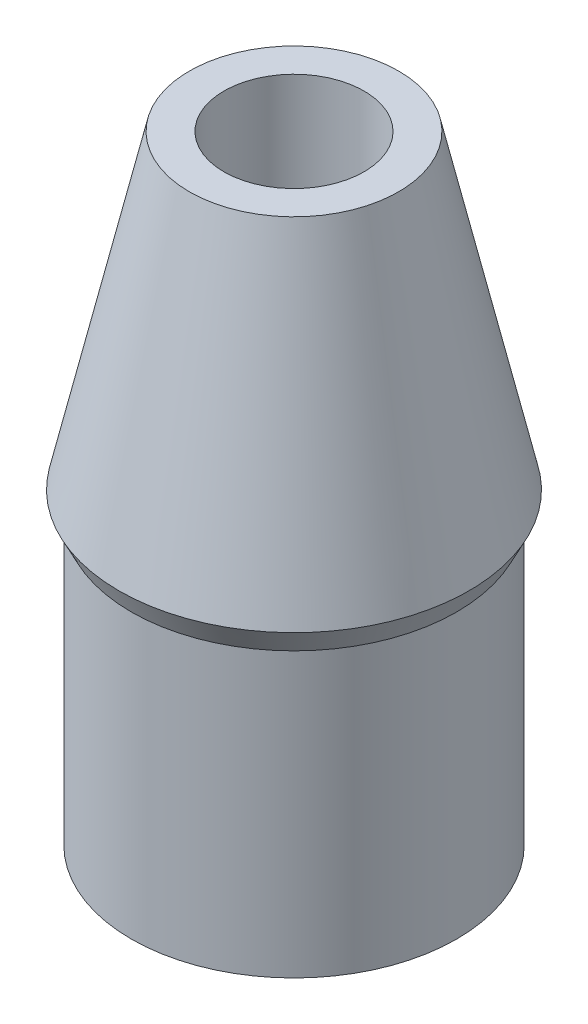
SolidWorks part; units mm, degrees
ref_plane "Front Plane" through (0, 0, 0) normal (0, 0, 1) x (1, 0, 0)
ref_plane "Top Plane" through (0, 0, 0) normal (0, 1, 0) x (1, 0, 0)
ref_plane "Right Plane" through (0, 0, 0) normal (1, 0, 0) x (0, 0, -1)
sketch "Sketch3" plane through (0, 0, 0) normal (0, 0, 1) x (1, 0, 0)
  line L0 (0, 16.51) -> (0, -13.97) construction
  line L1 (8.0264, -13.97) -> (0, -13.97)
  line L2 (5.1599, 16.51) -> (0, 16.51)
  line L3 (0, 16.51) -> (0, -13.97)
  line L7 (8.0264, 0) -> (8.0264, -13.97)
  line L10 (8.0264, 0) -> (8.6308, 1.204)
  line L11 (8.6308, 1.204) -> (5.1599, 16.51)
  dimension "D1" = 16.51
  dimension "D2" = 13.97
  dimension "D3" = 8.0264
revolve "Revolve1" add sketch "Sketch3" angle 360 about L0
hole_wizard "5/16-24 Tapped Hole2" positions "Sketch10" profile "Sketch9" tap size "5/16-24" standard "ANSI Inch"
sketch "Sketch10" plane through (0, 16.51, 0) normal (0, 1, 0) x (1, 0, 0)
  point P0 (0, 0)
sketch "Sketch9" plane through (0, 16.51, 0) normal (1, 0, 0) x (0, 0, 1)
  line L0 (0, 0) -> (0, 23.2465)
  line L1 (0, 23.2465) -> (3.4544, 21.1709)
  line L2 (3.4544, 21.1709) -> (3.4544, 0)
  line L5 (3.4544, 0) -> (0, 0)
  line L10 (0, 23.2465) -> (-3.4544, 21.1709) construction
  line L11 (0, -6.35) -> (0, 107.95) construction
  dimension "Tap Drill Dia." = 6.9088
  dimension "Tap Drill Depth" = 21.1709
  dimension "Drill Angle" = 118
cosmetic thread "Hole Thread2" parameters "D1"=15.875, "D2"=7.9375
